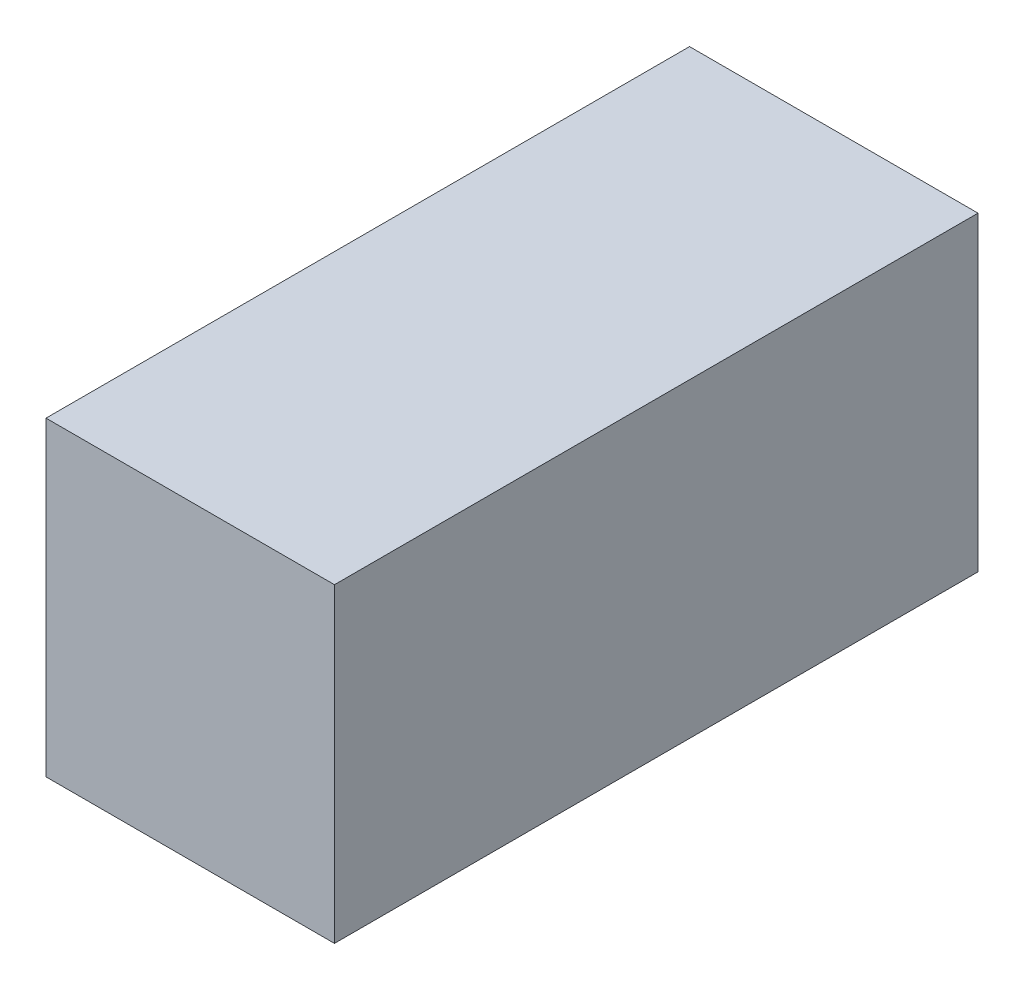
SolidWorks part; units mm, degrees
ref_plane "Front Plane" through (0, 0, 0) normal (0, 0, 1) x (1, 0, 0)
ref_plane "Top Plane" through (0, 0, 0) normal (0, 1, 0) x (1, 0, 0)
ref_plane "Right Plane" through (0, 0, 0) normal (1, 0, 0) x (0, 0, -1)
sketch "Sketch1" plane through (0, 0, 0) normal (0, 0, 1) x (1, 0, 0)
  line L5 (-30.4981, -38.6514) -> (47.5019, -38.6514)
  line L6 (-30.4981, -38.6514) -> (-30.4981, 45.3486)
  line L7 (-30.4981, 45.3486) -> (47.5019, 45.3486)
  line L8 (47.5019, -38.6514) -> (47.5019, 45.3486)
  line L9 (-30.4981, -38.6514) -> (47.5019, 45.3486) construction
  line L10 (-30.4981, 45.3486) -> (47.5019, -38.6514) construction
  point P0 (0, 0)
  point P1 (8.5019, 3.3486)
extrude "Boss-Extrude1" add sketch "Sketch1" along normal blind 174
